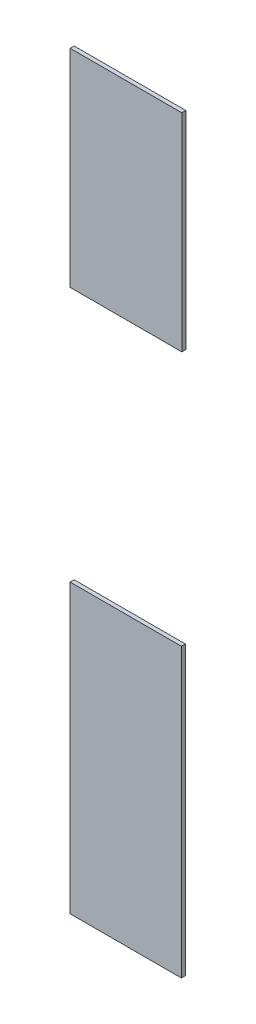
SolidWorks part; units mm, degrees
material "Гипс"
ref_plane "Спереди" through (0, 0, 0) normal (0, 0, 1) x (1, 0, 0)
ref_plane "Сверху" through (0, 0, 0) normal (0, 1, 0) x (1, 0, 0)
ref_plane "Справа" through (0, 0, 0) normal (1, 0, 0) x (0, 0, -1)
sketch "Эскиз3" plane through (0, 0, 0) normal (0, 0, 1) x (1, 0, 0)
  line L0 (-350, -650) -> (-350, 0) construction
  line L1 (0, 0) -> (-350, 0)
  line L2 (0, 0) -> (0, -649.25)
  line L3 (0, -649.25) -> (-350, -649.25)
  line L4 (-350, 0) -> (-350, -649.25)
  line L5 (-1600, -649.25) -> (0, -649.25) construction
  line L7 (-1.5, -1449.25) -> (-350, -1449.25)
  line L8 (-1.5, -1449.25) -> (-1.5, -2350)
  line L9 (-1.5, -2350) -> (-350, -2350)
  line L10 (-350, -1449.25) -> (-350, -2350)
extrude "Бобышка-Вытянуть1" add sketch "Эскиз3" along normal blind 12.5
